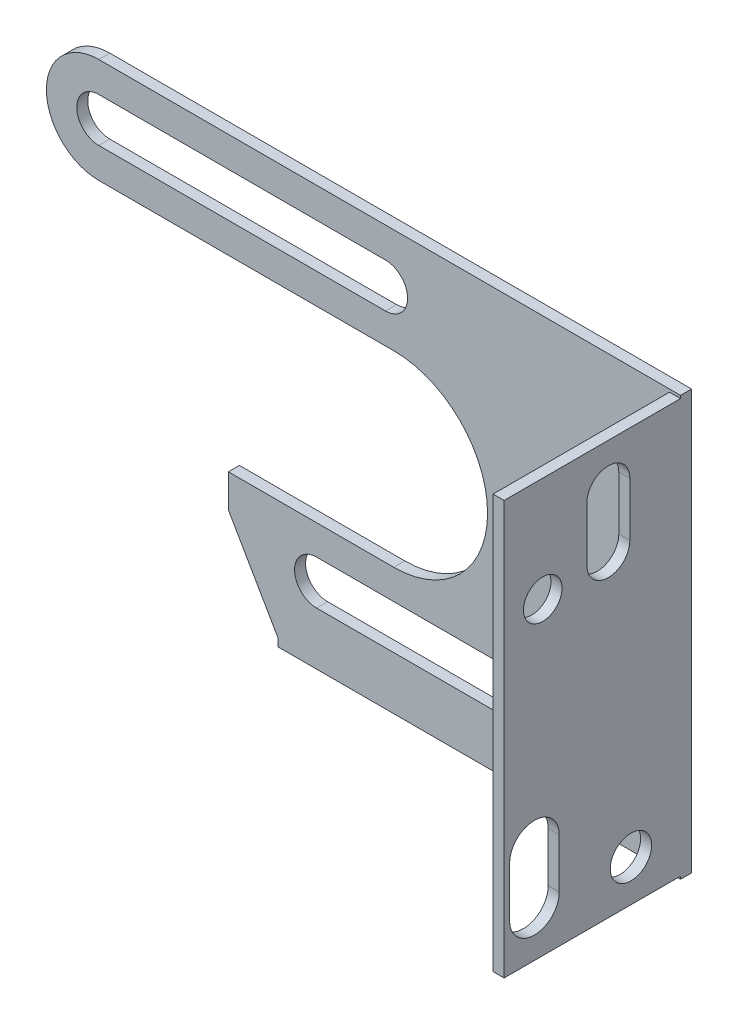
SolidWorks part; units mm, degrees
ref_plane "Front Plane" through (0, 0, 0) normal (0, 0, 1) x (1, 0, 0)
ref_plane "Top Plane" through (0, 0, 0) normal (0, 1, 0) x (1, 0, 0)
ref_plane "Right Plane" through (0, 0, 0) normal (1, 0, 0) x (0, 0, -1)
sketch "Sketch1" plane through (0, 0, 0) normal (0, 0, 1) x (1, 0, 0)
  line L1 (0, 0) -> (146.05, 0)
  line L2 (0, 0) -> (0, -101.6)
  line L3 (0, -101.6) -> (146.05, -101.6)
  line L4 (146.05, 0) -> (146.05, -101.6)
  dimension "D1" = 101.6
  dimension "D2" = 146.05
extrude "Boss-Extrude1" add sketch "Sketch1" along normal blind 2.54
sketch "Sketch2" plane through (0, 0, 0) normal (0, 0, 1) x (1, 0, 0)
  line L0 (0, 0) -> (0, -101.6) construction
  line L10 (0, -101.6) -> (146.05, -101.6) construction
  line L11 (146.05, -101.6) -> (146.05, 0) construction
  line L15 (80.01, -72.39) -> (41.91, -72.39)
  line L16 (41.91, -72.39) -> (41.91, -80.01)
  line L17 (41.91, -80.01) -> (53.34, -99.8073)
  line L18 (53.34, -99.8073) -> (53.34, -101.6)
  line L19 (53.34, -101.6) -> (0, -101.6)
  line L20 (0, -29.21) -> (0, -101.6)
  line L21 (12.065, -17.145) -> (78.105, -17.145) construction
  line L22 (12.065, -12.065) -> (78.105, -12.065)
  line L23 (12.065, -22.225) -> (78.105, -22.225)
  line L24 (146.05, 0) -> (0, 0) construction
  line L25 (62.23, -84.328) -> (128.27, -84.328) construction
  line L26 (62.23, -79.248) -> (128.27, -79.248)
  line L27 (62.23, -89.408) -> (128.27, -89.408)
  line L28 (80.01, -29.21) -> (12.065, -29.21)
  line L29 (0, -29.21) -> (-13.1361, -29.21)
  line L30 (-13.1361, -29.21) -> (-13.1361, 0)
  line L31 (-13.1361, 0) -> (146.05, 0)
  line L32 (146.05, 0) -> (146.05, -5.08)
  line L33 (146.05, -5.08) -> (12.065, -5.08)
  arc A0 (80.01, -29.21) -> (80.01, -72.39) centre (80.01, -50.8) cw
  arc A1 (12.065, -12.065) -> (12.065, -22.225) centre (12.065, -17.145) ccw
  arc A2 (78.105, -22.225) -> (78.105, -12.065) centre (78.105, -17.145) ccw
  arc A3 (62.23, -79.248) -> (62.23, -89.408) centre (62.23, -84.328) ccw
  arc A4 (128.27, -89.408) -> (128.27, -79.248) centre (128.27, -84.328) ccw
  arc A6 (12.065, -29.21) -> (12.065, -5.08) centre (12.065, -17.145) cw
  point P2 (45.085, -17.145)
  point P9 (6.985, -17.145)
  point P10 (83.185, -17.145)
  point P19 (146.05, -50.8)
  point P22 (101.6, -50.8)
  point P31 (95.25, -84.328)
  point P36 (57.15, -84.328)
  point P37 (133.35, -84.328)
  point P38 (0, -17.145)
  dimension "D2" = 76.2
  dimension "D3" = 6.985
  dimension "D4" = 12.065
  dimension "D5" = 10.16
  dimension "D6" = 76.2
  dimension "D7" = 10.16
  dimension "D8" = 12.192
  dimension "D9" = 38.1
  dimension "D10" = 44.45
  dimension "D11" = 7.62
  dimension "D12" = 22.86
  dimension "D13" = 12.7
  dimension "D15" = 30
extrude "Cut-Extrude1" cut sketch "Sketch2" along normal through all
ref_plane "Plane1" through (146.05, 0, 0) normal (-1, 0, 0) x (0, 0, 1)
sketch "Sketch4" plane through (146.05, 0, 0) normal (-1, 0, 0) x (0, 0, 1)
  line L0 (2.54, -5.715) -> (43.18, -5.715)
  line L1 (43.18, -5.715) -> (43.18, -100.965)
  line L2 (43.18, -100.965) -> (2.54, -100.965)
  line L3 (2.54, -99.8073) -> (2.54, -80.01) construction
  line L4 (2.54, -100.965) -> (2.54, -5.715)
  line L5 (2.54, -101.6) -> (2.54, -100.965) construction
  line L6 (2.54, -29.21) -> (2.54, -5.08) construction
  line L7 (2.54, -5.08) -> (2.54, -5.715) construction
  line L8 (19.177, -15.748) -> (19.177, -28.1559) construction
  line L9 (24.13, -15.748) -> (24.13, -28.1559)
  line L10 (14.224, -15.748) -> (14.224, -28.1559)
  line L11 (36.195, -78.74) -> (36.195, -90.17) construction
  line L12 (41.91, -78.74) -> (41.91, -90.17)
  line L13 (30.48, -78.74) -> (30.48, -90.17)
  line L14 (36.195, -78.74) -> (13.97, -78.74) construction
  arc A0 (24.13, -15.748) -> (14.224, -15.748) centre (19.177, -15.748) ccw
  arc A1 (14.224, -28.1559) -> (24.13, -28.1559) centre (19.177, -28.1559) ccw
  circle A2 centre (34.29, -29.845) radius 4.445
  arc A3 (41.91, -78.74) -> (30.48, -78.74) centre (36.195, -78.74) ccw
  arc A4 (30.48, -90.17) -> (41.91, -90.17) centre (36.195, -90.17) ccw
  circle A5 centre (13.97, -91.44) radius 4.7625
  point P15 (19.177, -21.9519)
  point P20 (19.177, -10.795)
  point P21 (19.177, -33.1089)
  point P25 (36.195, -84.455)
  point P30 (36.195, -95.885)
  point P31 (36.195, -73.025)
  dimension "D4" = 8.89
  dimension "D14" = 9.525
  dimension "D1" = 40.64
  dimension "D2" = 95.25
  dimension "D3" = 22.3139
  dimension "D5" = 8.89
  dimension "D6" = 19.05
  dimension "D7" = 5.08
  dimension "D8" = 9.906
  dimension "D9" = 24.13
  dimension "D10" = 6.985
  dimension "D11" = 11.43
  dimension "D12" = 22.86
  dimension "D13" = 5.08
  dimension "D15" = 9.525
  dimension "D16" = 29.21
extrude "Boss-Extrude2" add sketch "Sketch4" along normal blind 2.54
